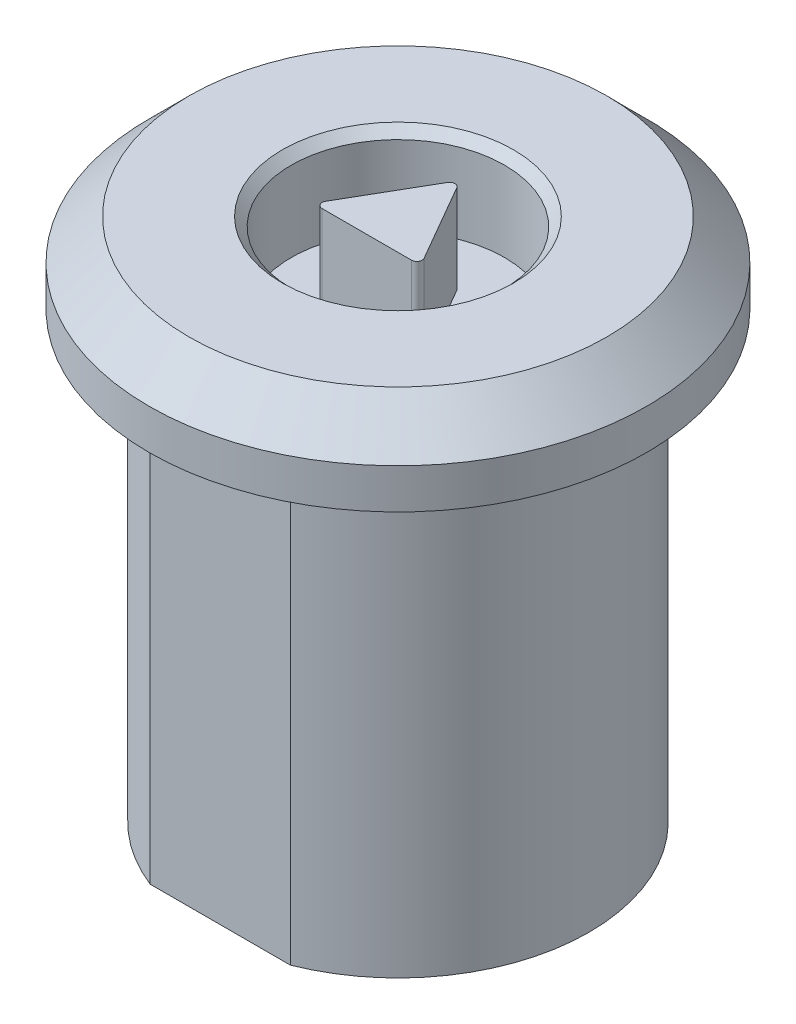
SolidWorks part; units mm, degrees
ref_plane "前视基准面" through (0, 0, 0) normal (0, 0, 1) x (1, 0, 0)
ref_plane "上视基准面" through (0, 0, 0) normal (0, 1, 0) x (1, 0, 0)
ref_plane "右视基准面" through (0, 0, 0) normal (1, 0, 0) x (0, 0, -1)
sketch "草图1" plane through (0, 0, 0) normal (0, 1, 0) x (1, 0, 0)
  circle A0 centre (0, 0) radius 14
  dimension "D1" = 28
extrude "凸台-拉伸1" add sketch "草图1" along normal blind 4.5
chamfer "倒角1" distance 2.25 angle 45 1 edges at (0, 4.5, 14)
sketch "草图2" plane through (0, 0, 0) normal (0, -1, 0) x (1, 0, 0)
  circle A0 centre (0, 0) radius 10.75
  dimension "D1" = 21.5
extrude "凸台-拉伸2" add sketch "草图2" along normal blind 25
sketch "草图3" plane through (0, -25, 0) normal (0, -1, 0) x (1, 0, 0)
  line L0 (-3.9449, -10) -> (3.9449, -10)
  line L1 (-3.9449, 10) -> (3.9449, 10)
  circle A0 centre (0, 0) radius 10.75 construction
  circle A1 centre (0, 0) radius 10.75 construction
  arc A2 (-3.9449, -10) -> (3.9449, -10) centre (0, 0) ccw
  arc A3 (-3.9449, 10) -> (3.9449, 10) centre (0, 0) cw
  dimension "D1" = 20
extrude "切除-拉伸1" cut sketch "草图3" against normal up to surface (25 mm away) up to face at (0, 0, 10.75)
sketch "草图4" plane through (0, 4.5, 0) normal (0, 1, 0) x (1, 0, 0)
  circle A0 centre (0, 0) radius 6
extrude "切除-拉伸2" cut sketch "草图4" against normal blind 5
sketch "草图5" plane through (0, -0.5, 0) normal (0, 1, 0) x (1, 0, 0)
  line L1 (-0.2598, 3.05) -> (-2.7713, -1.3)
  line L2 (-2.5115, -1.75) -> (2.5115, -1.75)
  line L3 (2.7713, -1.3) -> (0.2598, 3.05)
  circle A0 centre (0, 0) radius 3.5 construction
  arc A1 (2.5115, -1.75) -> (2.7713, -1.3) centre (2.5115, -1.45) ccw
  arc A2 (-2.5115, -1.75) -> (-2.7713, -1.3) centre (-2.5115, -1.45) cw
  arc A3 (0.2598, 3.05) -> (-0.2598, 3.05) centre (0, 2.9) ccw
  point P12 (0, 3.5)
  dimension "D1" = 7
  dimension "D2" = 0.3
extrude "凸台-拉伸3" add sketch "草图5" along normal up to surface (5 mm away) up to face at (0, 4.5, 6)
chamfer "倒角2" distance 0.5 angle 45 1 edges at (0, 4.5, 6)
sketch "草图6" plane through (0, -25, 0) normal (0, -1, 0) x (1, 0, 0)
  line L0 (0, -11.7683) -> (0, 11.5856) construction
  line L1 (7.0711, 0) -> (0, 7.0711)
  line L2 (0, 7.0711) -> (-7.0711, 0)
  line L3 (-7.0711, 0) -> (0, -7.0711)
  line L4 (0, -7.0711) -> (7.0711, 0)
  circle A0 centre (0, 0) radius 5 construction
  dimension "D1" = 10
extrude "凸台-拉伸4" add sketch "草图6" along normal blind 3
sketch "草图7" plane through (0, -28, 0) normal (0, -1, 0) x (1, 0, 0)
  circle A0 centre (0, 0) radius 2.5
  dimension "D1" = 5
extrude "切除-拉伸3" cut sketch "草图7" against normal blind 10
sketch "草图9" plane through (0, 0, 0) normal (0, 0, 1) x (1, 0, 0)
  line L0 (-7.0711, -27.4226) -> (-7.0711, -28)
  line L1 (-7.0711, -28) -> (-7.0711, -25) construction
  line L2 (-7.0711, -28) -> (-6.0711, -28)
  line L3 (0, -28) -> (-7.0711, -28) construction
  line L4 (-6.0711, -28) -> (-7.0711, -27.4226)
  line L5 (0, 0) -> (0, -48.8513) construction
  dimension "D1" = 1
  dimension "D2" = 30
revolve "切除-旋转3" cut sketch "草图9" angle 360 about L5
